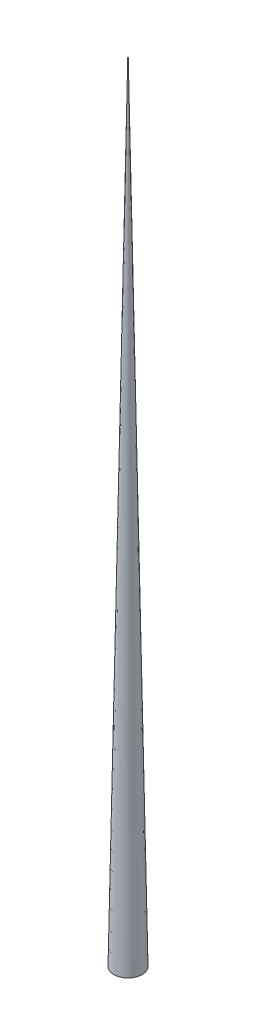
SolidWorks part; units mm, degrees
ref_plane "Front Plane" through (0, 0, 0) normal (0, 0, 1) x (1, 0, 0)
ref_plane "Top Plane" through (0, 0, 0) normal (0, 1, 0) x (1, 0, 0)
ref_plane "Right Plane" through (0, 0, 0) normal (1, 0, 0) x (0, 0, -1)
sketch "Sketch2" plane through (0, 0, 0) normal (1, 0, 0) x (0, 0, -1)
  line L0 (0, 0) -> (0, -228.6)
  line L1 (0, -228.6) -> (4.064, -228.6)
  line L2 (4.064, -228.6) -> (0, 0)
revolve "Revolve1" add sketch "Sketch2" angle 360 about L0
